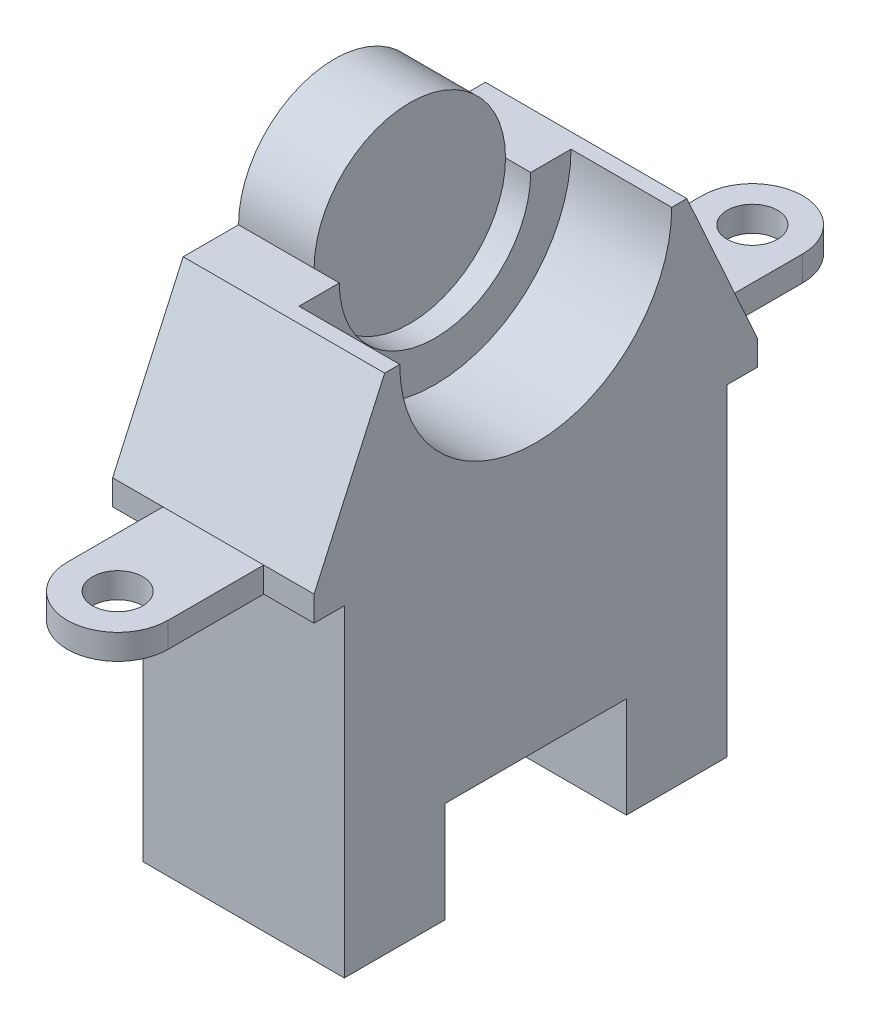
SolidWorks part; units mm, degrees
ref_plane "Front Plane" through (0, 0, 0) normal (0, 0, 1) x (1, 0, 0)
ref_plane "Top Plane" through (0, 0, 0) normal (0, 1, 0) x (1, 0, 0)
ref_plane "Right Plane" through (0, 0, 0) normal (1, 0, 0) x (0, 0, -1)
sketch "Sketch1" plane through (0, 0, 0) normal (1, 0, 0) x (0, 0, -1)
  line L0 (-38, 0) -> (-38, 64)
  line L1 (-38, 64) -> (-44, 64)
  line L2 (-44, 64) -> (-44, 69)
  line L3 (-44, 69) -> (-30, 100)
  line L4 (0, 55) -> (0, -55) construction
  line L5 (44, 69) -> (30, 100)
  line L6 (44, 64) -> (44, 69)
  line L7 (38, 64) -> (44, 64)
  line L8 (38, 0) -> (38, 64)
  line L9 (-30, 100) -> (30, 100)
  line L10 (-38, 0) -> (-18, 0)
  line L11 (-18, 0) -> (-18, 20)
  line L12 (-18, 20) -> (18, 20)
  line L13 (18, 20) -> (18, 0)
  line L14 (18, 0) -> (38, 0)
  line L15 (0, 0) -> (0, 85.0372) construction
  point P19 (0, 0)
  point P20 (-12.5587, 100)
  point P21 (0, 0)
  dimension "D1" = 76
  dimension "D2" = 36
  dimension "D3" = 20
  dimension "D4" = 5
  dimension "D5" = 6
  dimension "D6" = 100
  dimension "D7" = 60
  dimension "D8" = 64
extrude "Boss-Extrude1" add sketch "Sketch1" along normal mid plane 40
hole_wizard "Hole1" positions "Sketch2" profile "Sketch3" legacy
sketch "Sketch2" plane through (20, 0, 0) normal (1, 0, 0) x (0, 0, -1)
  line L0 (30, 100) -> (-30, 100) construction
  point P4 (0, 100)
sketch "Sketch3" plane through (20, 100, 0) normal (0, 1, 0) x (0, 0, -1)
  line L0 (0, 0) -> (0, 111.4164)
  line L1 (0, 111.4164) -> (19, 100)
  line L2 (19, 100) -> (19, 20)
  line L3 (19, 20) -> (27, 20)
  line L4 (27, 0) -> (0, 0)
  line L5 (0, -11.3109) -> (0, 121.1557) construction
  line L6 (0, 111.4164) -> (-19, 100) construction
  line L7 (27, 20) -> (27, 0)
  dimension "Depth" = 100
  dimension "Drill Angle" = 118
  dimension "Diameter" = 38
  dimension "C-Bore Diameter" = 54
  dimension "C-Bore Depth" = 20
sketch "Sketch4" plane through (-20, 0, 0) normal (-1, 0, 0) x (0, 0, 1)
  circle A0 centre (0, 100) radius 19
  point P5 (0, 92)
  dimension "D1" = 38
  dimension "D2" = 100
extrude "Boss-Extrude2" add sketch "Sketch4" against normal blind 15
ref_plane "Plane1" through (0, 69, 0) normal (0, 1, 0) x (1, 0, 0)
sketch "Sketch5" plane through (0, 69, 0) normal (0, 1, 0) x (1, 0, 0)
  line L0 (-10, 63) -> (-10, 44)
  line L1 (10, 63) -> (10, 44)
  line L2 (20, 44) -> (-20, 44) construction
  line L3 (10, 44) -> (-10, 44)
  arc A0 (10, 63) -> (-10, 63) centre (0, 63) ccw
  circle A1 centre (0, 63) radius 5
  dimension "D1" = 20
  dimension "D2" = 10
  dimension "D3" = 63
extrude "Boss-Extrude3" add sketch "Sketch5" against normal up to surface (5 mm away) up to face at (0, 64, -41)
mirror "Mirror1" about plane through (0, 0, 0) normal (0, 0, 1) of "Boss-Extrude3"
